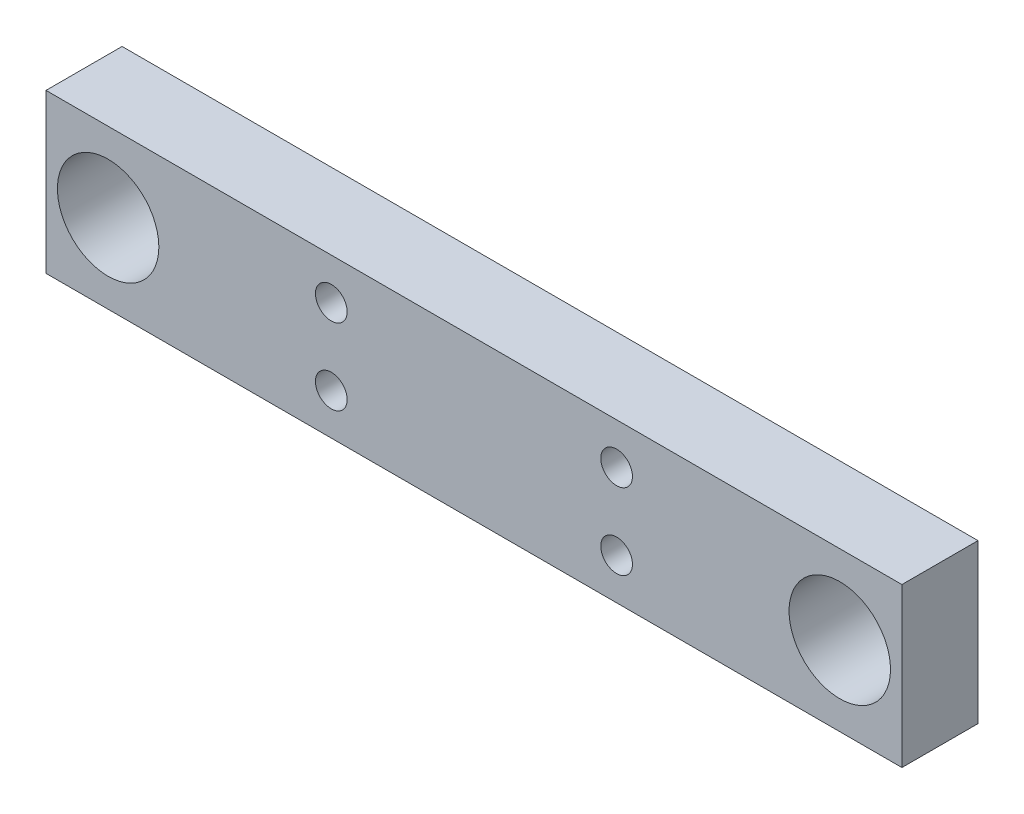
SolidWorks part; units mm, degrees
ref_plane "Front Plane" through (0, 0, 0) normal (0, 0, 1) x (1, 0, 0)
ref_plane "Top Plane" through (0, 0, 0) normal (0, 1, 0) x (1, 0, 0)
ref_plane "Right Plane" through (0, 0, 0) normal (1, 0, 0) x (0, 0, -1)
sketch "Sketch1" plane through (0, 0, 0) normal (0, 0, 1) x (1, 0, 0)
  line L0 (0, 0) -> (0, 10.1407) construction
  line L1 (-67.5, -12.5) -> (67.5, -12.5)
  line L2 (-67.5, -12.5) -> (-67.5, 12.5)
  line L3 (-67.5, 12.5) -> (67.5, 12.5)
  line L4 (67.5, -12.5) -> (67.5, 12.5)
  line L5 (-67.5, -12.5) -> (67.5, 12.5) construction
  line L6 (-67.5, 12.5) -> (67.5, -12.5) construction
  line L7 (0, 0) -> (19.0237, 0) construction
  point P0 (0, 0)
  dimension "D2" = 135
  dimension "D3" = 25
extrude "Boss-Extrude1" add sketch "Sketch1" along normal mid plane 12 contours L2 L3 L4 L1
sketch "Sketch2" plane through (0, 0, 6) normal (0, 0, 1) x (1, 0, 0)
  line L0 (0, 0) -> (0, 25.0835) construction
  line L1 (0, 0) -> (17.8331, 0) construction
  circle A0 centre (-57.7, 0) radius 8
  circle A1 centre (57.7, 0) radius 8
  point P0 (-57.7, 0)
  point P1 (57.7, 0)
  point P5 (22.5, 6)
  point P6 (22.5, -6)
  point P9 (-22.5, -6)
  point P10 (-22.5, 6)
  dimension "D4" = 16
  dimension "D5" = 16
  dimension "D1" = 115.4
  dimension "D2" = 45
  dimension "D3" = 12
hole_wizard "Tap Drill for M6x1.0 Tap1" positions "Sketch3" profile "Sketch4" hole size "M6x1.0" standard "ANSI Metric" end condition up to next
sketch "Sketch3" plane through (0, 0, 6) normal (0, 0, 1) x (1, 0, 0)
  point P0 (-22.5, 6)
  point P3 (-22.5, -6)
  point P6 (22.5, 6)
  point P9 (22.5, -6)
sketch "Sketch4" plane through (-22.5, 6, 6) normal (1, 0, 0) x (0, -1, 0)
  line L0 (0, 0) -> (0, 12)
  line L1 (0, 12) -> (2.5, 12)
  line L2 (2.5, 12) -> (2.5, 0)
  line L5 (2.5, 0) -> (0, 0)
  line L11 (0, -6.35) -> (0, 107.95) construction
  dimension "Thru Hole Dia." = 5
  dimension "Thru Hole Depth" = 12
extrude "Cut-Extrude1" cut sketch "Sketch2" against normal through all
